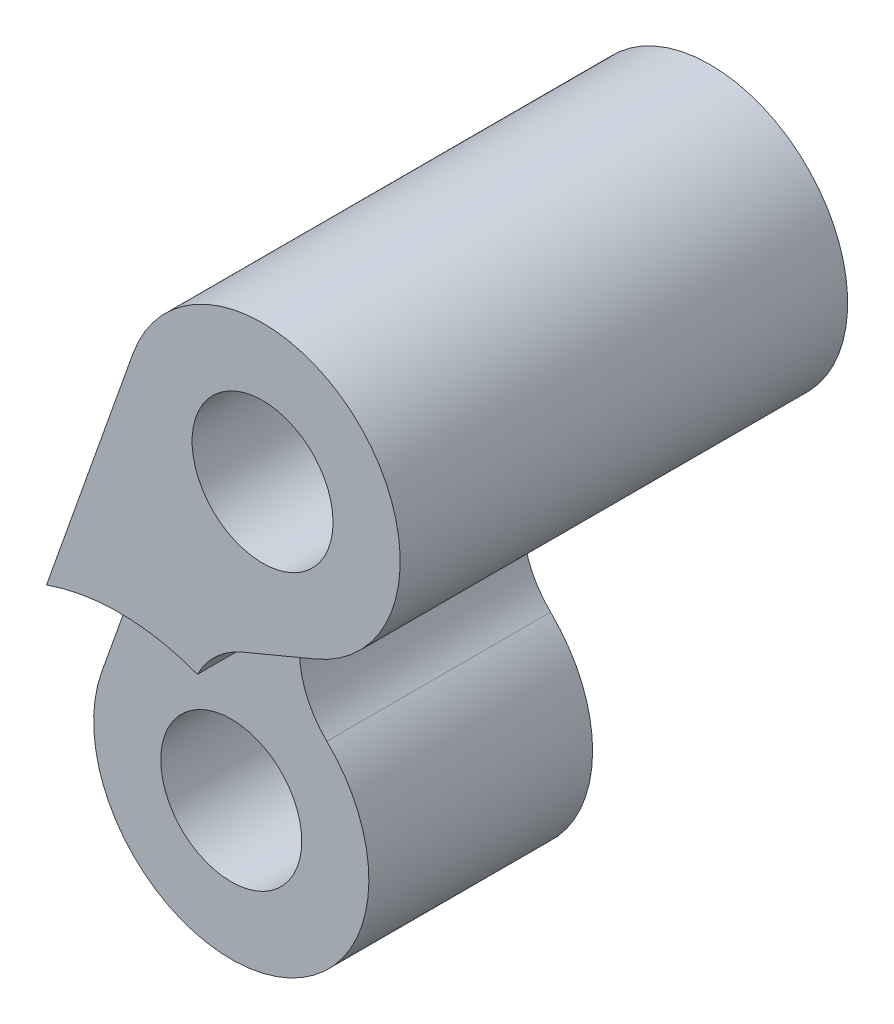
SolidWorks part; units mm, degrees
ref_plane "Front" through (0, 0, 0) normal (0, 0, 1) x (1, 0, 0)
ref_plane "Top" through (0, 0, 0) normal (0, 1, 0) x (1, 0, 0)
ref_plane "Right" through (0, 0, 0) normal (1, 0, 0) x (0, 0, -1)
sketch "Sketch1" plane through (0, 0, 0) normal (0, 0, 1) x (1, 0, 0)
  line L3 (-3.075, 0) -> (-1.575, 0) construction
  line L11 (-4.7748, -9.0162) -> (-6.2748, -9.0162) construction
  line L17 (0, -3.5218) -> (3.05, -1.7609) construction
  line L18 (1.1861, -2.837) -> (-0.4466, -3.5196)
  line L21 (-2.8979, 1.0284) -> (-6.0977, -7.9878)
  circle A0 centre (0, 0) radius 3.075 construction
  circle A3 centre (0, 0) radius 1.575
  circle A12 centre (-3.1998, -9.0162) radius 1.575
  circle A13 centre (-3.1998, -9.0162) radius 3.075 construction
  arc A14 (1.1861, -2.837) -> (-2.8979, 1.0284) centre (0, 0) ccw
  arc A20 (-0.4466, -3.5196) -> (-1.0642, -6.8038) centre (0.3249, -5.3649) ccw
  arc A21 (-1.0642, -6.8038) -> (-6.0977, -7.9878) centre (-3.1998, -9.0162) cw
  point P15 (-5.9748, -6.1916)
  point P17 (-6.2748, -7.5162)
  point P29 (0.4341, -11.7326)
  point P30 (0, 0)
  point P33 (0.4789, -3.1327)
  point P35 (1.1861, -4.9889)
  point P36 (0, 0)
  point P37 (-6.2748, -8.4537)
  point P38 (-0.2531, -8.3951)
  dimension "D1" = 3.15
  dimension "D5" = 2
  dimension "D2" = 1.5
extrude "Boss-Extrude1" add sketch "Sketch1" along normal mid plane 10
sketch "Sketch2" plane through (0, 0, 5) normal (0, 0, 1) x (1, 0, 0)
  circle A0 centre (-3.1998, -9.0162) radius 4.8845
extrude "Cut-Extrude1" cut sketch "Sketch2" against normal blind 2.5
mirror "Mirror1" about plane through (0, 0, 0) normal (0, 0, 1) of "Cut-Extrude1"
equation "\"D1@Sketch1\"=\"Hardware Clearance Hole Diameter@Box Assy.Assembly\""
